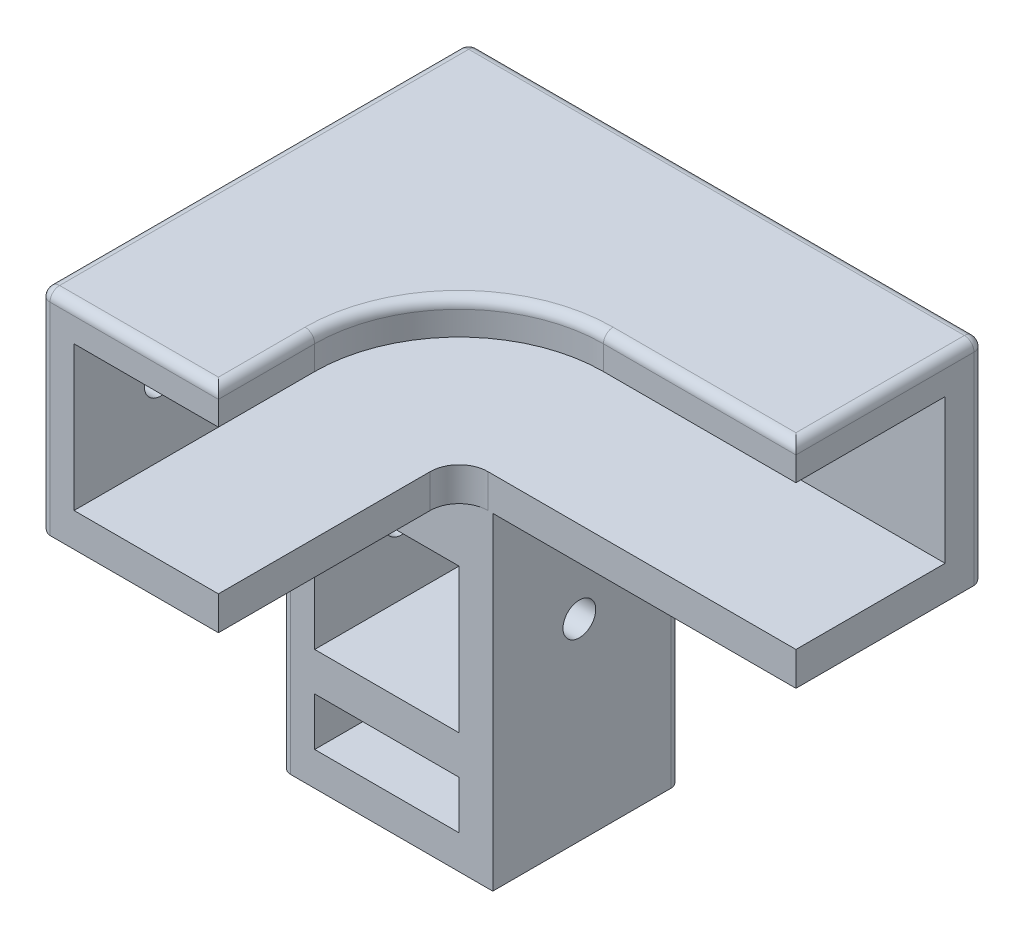
SolidWorks part; units mm, degrees
ref_plane "Front Plane" through (0, 0, 0) normal (0, 0, 1) x (1, 0, 0)
ref_plane "Top Plane" through (0, 0, 0) normal (0, 1, 0) x (1, 0, 0)
ref_plane "Right Plane" through (0, 0, 0) normal (1, 0, 0) x (0, 0, -1)
sketch "Sketch1" plane through (0, 0, 0) normal (0, 0, 1) x (1, 0, 0)
  line L1 (-5.6994, 32.9163) -> (16.3006, 32.9163)
  line L2 (-5.6994, 10.9163) -> (-5.6994, -23.0837)
  line L3 (-5.6994, -23.0837) -> (16.3006, -23.0837)
  line L4 (16.3006, 32.9163) -> (16.3006, -23.0837)
  line L5 (-5.6994, 10.9163) -> (-37.1994, 10.9163)
  line L7 (-5.6994, 32.9163) -> (-37.1994, 32.9163)
  line L8 (-37.1994, 10.9163) -> (-37.1994, 32.9163)
  dimension "D1" = 22
  dimension "D2" = 22
  dimension "D3" = 56
  dimension "D4" = 53.5
extrude "Boss-Extrude1" add sketch "Sketch1" along normal blind 19.5
sketch "Sketch3" plane through (0, 0, 19.5) normal (0, 0, 1) x (1, 0, 0)
  line L1 (16.3006, 32.9163) -> (-2.1994, 32.9163)
  line L2 (16.3006, 32.9163) -> (16.3006, 10.9163)
  line L3 (16.3006, 10.9163) -> (-2.1994, 10.9163)
  line L4 (-2.1994, 32.9163) -> (-2.1994, 10.9163)
  dimension "D1" = 18.5
extrude "Boss-Extrude2" add sketch "Sketch3" along normal blind 25
sketch "Sketch5" plane through (0, 0, 44.5) normal (0, 0, 1) x (1, 0, 0)
  line L0 (-37.1994, 32.9163) -> (-37.1994, 10.9163) construction
  line L1 (-37.1994, 29.4163) -> (12.8006, 29.4163)
  line L2 (-37.1994, 29.4163) -> (-37.1994, 14.4163)
  line L3 (-37.1994, 14.4163) -> (12.8006, 14.4163)
  line L4 (12.8006, 29.4163) -> (12.8006, 14.4163)
  line L5 (16.3006, 10.9163) -> (16.3006, 32.9163) construction
  line L6 (-2.1994, 4.4163) -> (12.8006, 4.4163)
  line L7 (-2.1994, 4.4163) -> (-2.1994, -10.5837)
  line L8 (-2.1994, -10.5837) -> (12.8006, -10.5837)
  line L9 (12.8006, 4.4163) -> (12.8006, -10.5837)
  line L12 (-2.1994, 32.9163) -> (-37.1994, 32.9163) construction
  line L13 (-2.1994, 10.9163) -> (16.3006, 10.9163) construction
  line L15 (16.3006, -23.0837) -> (16.3006, 10.9163) construction
  line L16 (-5.6994, -23.0837) -> (16.3006, -23.0837) construction
  line L17 (-2.1994, -14.5837) -> (12.8006, -14.5837)
  line L18 (-2.1994, -14.5837) -> (-2.1994, -19.5837)
  line L19 (-2.1994, -19.5837) -> (12.8006, -19.5837)
  line L20 (12.8006, -14.5837) -> (12.8006, -19.5837)
  dimension "D1" = 3.5
  dimension "D2" = 6.5
  dimension "D3" = 15
  dimension "D4" = 3.5
  dimension "D5" = 15
  dimension "D6" = 15
  dimension "D7" = 3.5
  dimension "D8" = 15
  dimension "D9" = 4
  dimension "D10" = 3.5
extrude "Cut-Extrude1" cut sketch "Sketch5" against normal offset from surface (40.5 mm away) 4 up to face at (-8.8661, 6.9163, 0)
sketch "Sketch7" plane through (16.3006, 0, 0) normal (1, 0, 0) x (0, 0, -1)
  line L0 (-34.5, 10.9163) -> (-19.5, 10.9163)
  line L1 (-44.5, 10.9163) -> (-19.5, 10.9163) construction
  line L2 (-19.5, 10.9163) -> (-19.5, -4.0837)
  line L3 (-19.5, -23.0837) -> (-19.5, 10.9163) construction
  arc A0 (-34.5, 10.9163) -> (-19.5, -4.0837) centre (-34.5, -4.0837) cw
  dimension "D1" = 15
extrude "Boss-Extrude4" add sketch "Sketch7" against normal blind 3.5
sketch "Sketch8" plane through (0, 0, 0) normal (0, 0, -1) x (-1, 0, 0)
  line L0 (5.6994, 10.9163) -> (20.6994, 10.9163)
  line L1 (37.1994, 10.9163) -> (5.6994, 10.9163) construction
  line L2 (5.6994, 10.9163) -> (5.6994, -4.0837)
  line L3 (5.6994, 10.9163) -> (5.6994, -23.0837) construction
  arc A0 (20.6994, 10.9163) -> (5.6994, -4.0837) centre (20.6994, -4.0837) ccw
  dimension "D1" = 15
extrude "Boss-Extrude5" add sketch "Sketch8" against normal blind 3.5
sketch "Sketch9" plane through (0, 32.9163, 0) normal (0, 1, 0) x (1, 0, 0)
  line L0 (-2.1994, -34.5) -> (-2.1994, -19.5)
  line L1 (-2.1994, -44.5) -> (-2.1994, -19.5) construction
  line L2 (-2.1994, -19.5) -> (-17.1994, -19.5)
  line L3 (-2.1994, -19.5) -> (-37.1994, -19.5) construction
  arc A0 (-2.1994, -34.5) -> (-17.1994, -19.5) centre (-17.1994, -34.5) ccw
  dimension "D1" = 15
extrude "Boss-Extrude6" add sketch "Sketch9" against normal blind 3.5
fillet "Fillet3" radius 3 1 edges
sketch "Sketch11" plane through (0, 0, 0) normal (0, 0, -1) x (-1, 0, 0)
  line L0 (1.1994, -23.0837) -> (1.1994, 10.9163) construction
  line L2 (5.6994, -23.0837) -> (-16.3006, -23.0837) construction
  line L5 (5.6994, -4.0837) -> (5.6994, -23.0837) construction
  text T0 "MR.3" font "Century Gothic" height 12
  dimension "D1" = 4.5
extrude "Cut-Extrude3" cut sketch "Sketch11" against normal blind 1
sketch "Sketch12" plane through (0, 0, 0) normal (0, 0, -1) x (-1, 0, 0)
  line L0 (37.1994, 21.9163) -> (-16.3006, 21.9163) construction
  line L1 (37.1994, 32.9163) -> (37.1994, 10.9163) construction
  line L2 (-16.3006, -23.0837) -> (-16.3006, 32.9163) construction
  line L3 (-12.8006, 14.4163) -> (-12.8006, 29.4163) construction
  circle A0 centre (-5.3006, 21.9163) radius 1.7
  circle A1 centre (10.9494, 21.9163) radius 1.7
  circle A2 centre (27.1994, 21.9163) radius 1.7
  dimension "D4" = 3.4
  dimension "D1" = 7.5
  dimension "D2" = 10
  dimension "D3" = 16.25
extrude "Cut-Extrude4" cut sketch "Sketch12" against normal blind 5
sketch "Sketch13" plane through (-5.6994, 0, 0) normal (-1, 0, 0) x (0, 0, 1)
  line L0 (4, 4.4163) -> (19.5, 4.4163) construction
  line L1 (19.5, 10.9163) -> (19.5, -23.0837) construction
  circle A0 centre (10.5, -3.0837) radius 1.7
  dimension "D2" = 9
  dimension "D3" = 3.4
  dimension "D1" = 7.5
extrude "Cut-Extrude5" cut sketch "Sketch13" against normal blind 45
sketch "Sketch14" plane through (16.3006, 0, 0) normal (1, 0, 0) x (0, 0, -1)
  line L0 (-10.5, -3.0837) -> (-10.5, 32.9163) construction
  line L1 (-44.5, 32.9163) -> (0, 32.9163) construction
  line L2 (-44.5, 21.9163) -> (-10.5, 21.9163) construction
  line L3 (-44.5, 10.9163) -> (-44.5, 32.9163) construction
  circle A0 centre (-10.5, 21.9163) radius 1.7
  circle A1 centre (-35.5, 21.9163) radius 1.7
  dimension "D1" = 3.4
  dimension "D2" = 9
extrude "Cut-Extrude6" cut sketch "Sketch14" against normal blind 45
sketch "Sketch15" plane through (0, -23.0837, 0) normal (0, -1, 0) x (1, 0, 0)
  line L0 (16.3006, 9.75) -> (-5.6994, 9.75) construction
  line L1 (16.3006, 19.5) -> (16.3006, 0) construction
  line L2 (-5.6994, 19.5) -> (-5.6994, 0) construction
  line L3 (5.3006, 19.5) -> (5.3006, 0) construction
  line L4 (-5.6994, 19.5) -> (16.3006, 19.5) construction
  line L5 (-5.6994, 0) -> (16.3006, 0) construction
  circle A0 centre (5.3006, 9.75) radius 1.7
  dimension "D1" = 3.4
extrude "Cut-Extrude7" cut sketch "Sketch15" against normal blind 4
mirror "Mirror2" about plane through (16.3006, 32.9163, 19.5) normal (-1, 0, 0) of "Cut-Extrude7", "Cut-Extrude6", "Cut-Extrude5", "Cut-Extrude4", "Fillet3", "Boss-Extrude6", "Boss-Extrude5", "Boss-Extrude4", "Cut-Extrude1", "Boss-Extrude2", "Boss-Extrude1"
sketch "Sketch16" plane through (0, 0, 0) normal (0, 0, -1) x (-1, 0, 0)
  line L0 (-69.8006, 32.9163) -> (37.1994, 32.9163) construction
  line L1 (-16.3006, 32.9163) -> (53.9943, 32.9163)
  line L2 (-16.3006, 32.9163) -> (-16.3006, -24.95)
  line L3 (-16.3006, -24.95) -> (53.9943, -24.95)
  line L4 (53.9943, 32.9163) -> (53.9943, -24.95)
extrude "Cut-Extrude8" cut sketch "Sketch16" against normal blind 72
sketch "Sketch20" plane through (0, 0, 0) normal (0, 0, -1) x (-1, 0, 0)
  line L0 (-22.3006, -23.0837) -> (-22.3006, 16.9163) construction
  line L1 (-16.3006, -23.0837) -> (-38.3006, -23.0837) construction
  line L2 (-16.3006, 32.9163) -> (-16.3006, -23.0837) construction
  text T0 "ALFR3D" font "Murder Of Mayday" height 10
  dimension "D1" = 6
  dimension "D2" = 40
extrude "Cut-Extrude9" [suppressed] cut sketch "Sketch20" against normal blind 1
fillet "Fillet4" radius 1 17 edges at (25.5506, 32.9163, 44.5) (69.8006, 32.9163, 9.75) (69.8006, 21.9163, 0) (61.5506, 10.9163, 0) (34.8006, 32.9163, 39.5) (38.3006, -13.5837, 0) (42.694, 6.5229, 0) (39.194, 32.9163, 23.8934) (16.3006, 32.9163, 22.25) (16.3006, 4.9163, 0) (16.3006, 21.9163, 44.5) (16.3006, 10.9163, 39.5) (16.3006, -13.5837, 19.5) (16.3006, 6.5229, 23.8934) (43.0506, 32.9163, 0)
